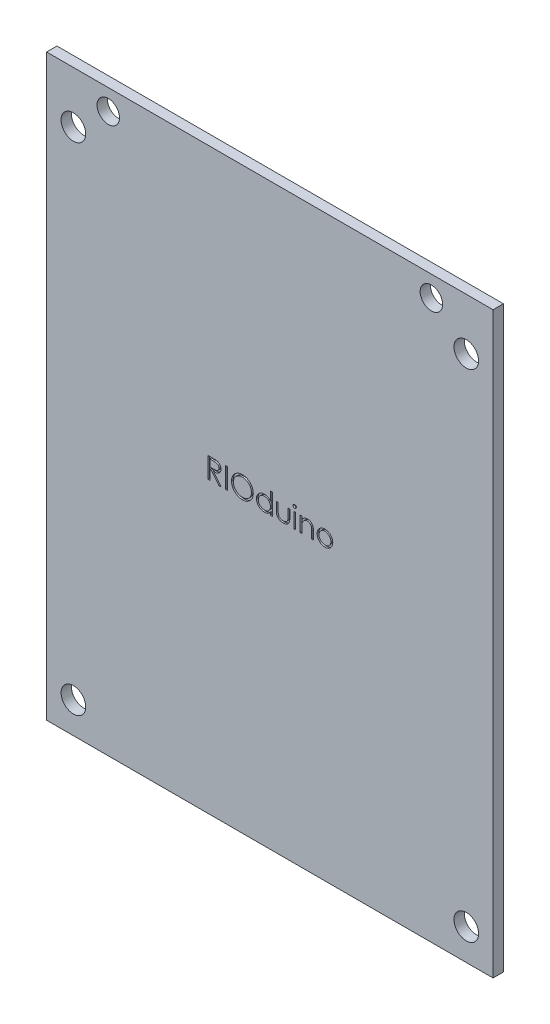
SolidWorks part; units mm, degrees
material "ABS"
ref_plane "Front Plane" through (0, 0, 0) normal (0, 0, 1) x (1, 0, 0)
ref_plane "Top Plane" through (0, 0, 0) normal (0, 1, 0) x (1, 0, 0)
ref_plane "Right Plane" through (0, 0, 0) normal (1, 0, 0) x (0, 0, -1)
sketch "Sketch1" plane through (0, 0, 0) normal (0, 0, 1) x (1, 0, 0)
  line L1 (-34.29, -44.45) -> (34.29, -44.45)
  line L2 (-34.29, -44.45) -> (-34.29, 44.45)
  line L3 (-34.29, 44.45) -> (34.29, 44.45)
  line L4 (34.29, -44.45) -> (34.29, 44.45)
  line L5 (-34.29, -44.45) -> (34.29, 44.45) construction
  line L6 (-34.29, 44.45) -> (34.29, -44.45) construction
  point P0 (0, 0)
  dimension "D1" = 68.58
  dimension "D2" = 88.9
extrude "Boss-Extrude1" add sketch "Sketch1" along normal blind 1.5875
sketch "Sketch2" plane through (0, 0, 1.5875) normal (0, 0, 1) x (1, 0, 0)
  line L0 (0, 44.45) -> (0, -44.45) construction
  line L1 (34.29, 44.45) -> (-34.29, 44.45) construction
  line L2 (-34.29, -44.45) -> (34.29, -44.45) construction
  line L3 (34.29, -44.45) -> (34.29, 44.45) construction
  circle A0 centre (-24.8158, 41.275) radius 1.7272
  circle A1 centre (-30.1752, 36.5252) radius 1.8923
  circle A2 centre (-30.1752, -39.6748) radius 1.8923
  circle A3 centre (30.1752, -39.6748) radius 1.8923
  circle A4 centre (24.8158, 41.275) radius 1.7272
  circle A5 centre (30.1752, 36.5252) radius 1.8923
  dimension "D1" = 3.4544
  dimension "D2" = 3.7846
  dimension "D3" = 3.7846
  dimension "D4" = 24.8158
  dimension "D5" = 64.4652
  dimension "D6" = 85.725
  dimension "D7" = 80.9752
  dimension "D8" = 64.4652
  dimension "D9" = 4.7752
extrude "Cut-Extrude1" cut sketch "Sketch2" against normal through all
sketch "Sketch3" plane through (0, 0, 1.5875) normal (0, 0, 1) x (1, 0, 0)
  line L0 (-34.29, 0) -> (34.29, 0) construction
  line L1 (-34.29, 44.45) -> (-34.29, -44.45) construction
  line L2 (34.29, -44.45) -> (34.29, 44.45) construction
  text T0 "RIOduino"
extrude "Cut-Extrude2" cut sketch "Sketch3" against normal blind 0.254
